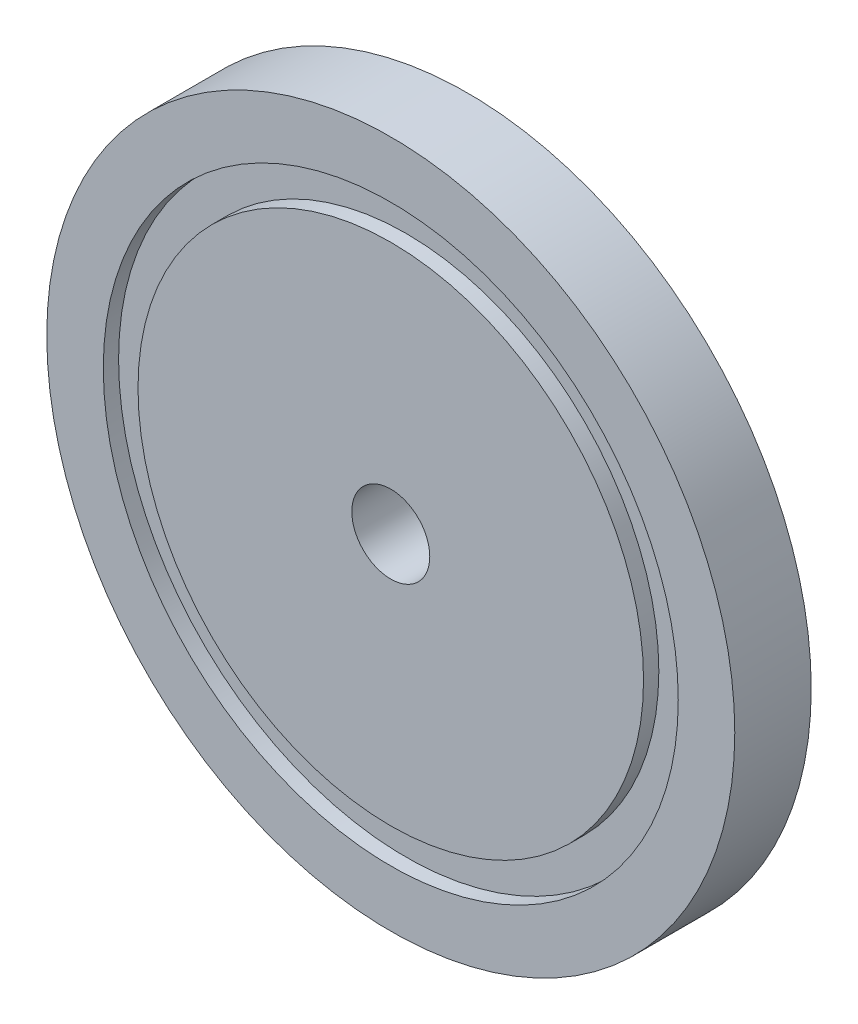
SolidWorks part; units mm, degrees
ref_plane "Plan de face" through (0, 0, 0) normal (0, 0, 1) x (1, 0, 0)
ref_plane "Plan de dessus" through (0, 0, 0) normal (0, 1, 0) x (1, 0, 0)
ref_plane "Plan de droite" through (0, 0, 0) normal (1, 0, 0) x (0, 0, -1)
sketch "Esquisse1" plane through (0, 0, 0) normal (0, 0, 1) x (1, 0, 0)
  circle A0 centre (0, 0) radius 22.5
  dimension "D1" = 45
extrude "Boss.-Extru.1" add sketch "Esquisse1" along normal blind 5
sketch "Esquisse6" plane through (0, 0, 5) normal (0, 0, 1) x (1, 0, 0)
  circle A1 centre (0, 0) radius 2.55
  dimension "D1" = 5.1
extrude "Enlèv. mat.-Extru.4" cut sketch "Esquisse6" against normal blind 5
sketch "Esquisse7" plane through (0, 0, 5) normal (0, 0, 1) x (1, 0, 0)
  circle A0 centre (0, 0) radius 18.8031
  circle A1 centre (0, 0) radius 16.5325
extrude "Enlèv. mat.-Extru.5" cut sketch "Esquisse7" against normal blind 1
